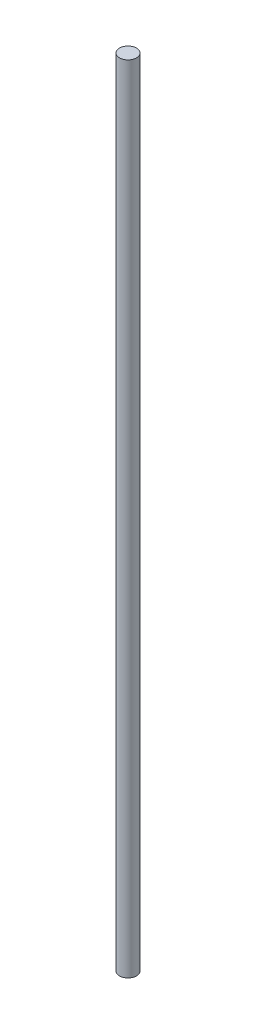
SolidWorks part; units mm, degrees
ref_plane "Front Plane" through (0, 0, 0) normal (0, 0, 1) x (1, 0, 0)
ref_plane "Top Plane" through (0, 0, 0) normal (0, 1, 0) x (1, 0, 0)
ref_plane "Right Plane" through (0, 0, 0) normal (1, 0, 0) x (0, 0, -1)
sketch "Sketch1" plane through (0, 0, 0) normal (0, 0, 1) x (1, 0, 0)
  line L0 (1.5, 140) -> (0, 140)
  line L1 (0, 140) -> (0, 0)
  line L2 (0, 0) -> (1.5, 0)
  line L3 (1.5, 0) -> (1.5, 140)
  line L4 (0, 140) -> (0, 0) construction
revolve "Revolve1" add sketch "Sketch1" angle 360 about L4
